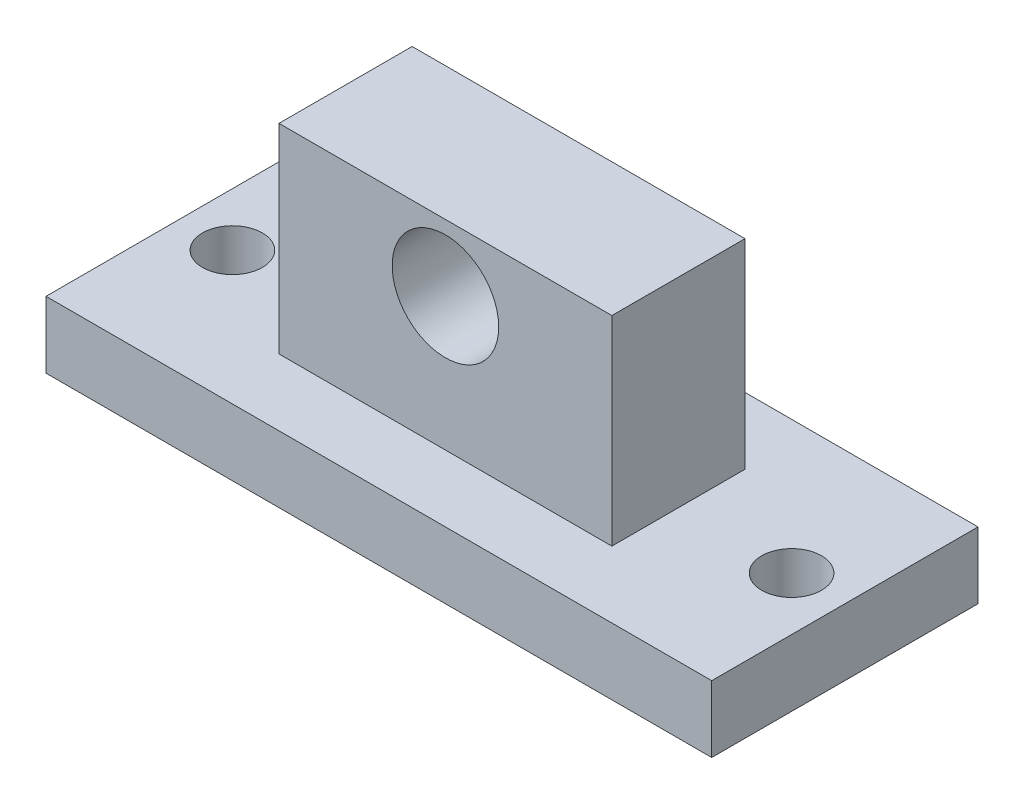
SolidWorks part; units mm, degrees
material "ABS"
ref_plane "Front Plane" through (0, 0, 0) normal (0, 0, 1) x (1, 0, 0)
ref_plane "Top Plane" through (0, 0, 0) normal (0, 1, 0) x (1, 0, 0)
ref_plane "Right Plane" through (0, 0, 0) normal (1, 0, 0) x (0, 0, -1)
sketch "Sketch1" plane through (0, 0, 0) normal (0, 1, 0) x (1, 0, 0)
  line L1 (-25, -10) -> (25, -10)
  line L2 (-25, -10) -> (-25, 10)
  line L3 (-25, 10) -> (25, 10)
  line L4 (25, -10) -> (25, 10)
  line L5 (-25, -10) -> (25, 10) construction
  line L6 (-25, 10) -> (25, -10) construction
  point P0 (0, 0)
  dimension "D1" = 20
  dimension "D2" = 50
extrude "Boss-Extrude1" add sketch "Sketch1" along normal blind 5
sketch "Sketch2" plane through (0, 5, 0) normal (0, 1, 0) x (1, 0, 0)
  line L1 (-25, 10) -> (-25, -10) construction
  circle A0 centre (-21, 0) radius 2.25
  circle A1 centre (21, 0) radius 2.25
  dimension "D1" = 4.5
  dimension "D2" = 4.5
  dimension "D3" = 42
  dimension "D4" = 4
extrude "Cut-Extrude1" cut sketch "Sketch2" against normal blind 5
sketch "Sketch3" plane through (0, 5, 0) normal (0, 1, 0) x (1, 0, 0)
  line L1 (-12.5, -5) -> (12.5, -5)
  line L2 (-12.5, -5) -> (-12.5, 5)
  line L3 (-12.5, 5) -> (12.5, 5)
  line L4 (12.5, -5) -> (12.5, 5)
  line L5 (-12.5, -5) -> (12.5, 5) construction
  line L6 (-12.5, 5) -> (12.5, -5) construction
  point P0 (0, 0)
  dimension "D1" = 10
  dimension "D2" = 25
extrude "Boss-Extrude2" add sketch "Sketch3" along normal blind 15
sketch "Sketch4" plane through (0, 0, 5) normal (0, 0, 1) x (1, 0, 0)
  line L1 (-25, 0) -> (25, 0) construction
  circle A0 centre (0, 15) radius 4
  dimension "D1" = 8
  dimension "D2" = 15
extrude "Cut-Extrude2" cut sketch "Sketch4" against normal blind 15
